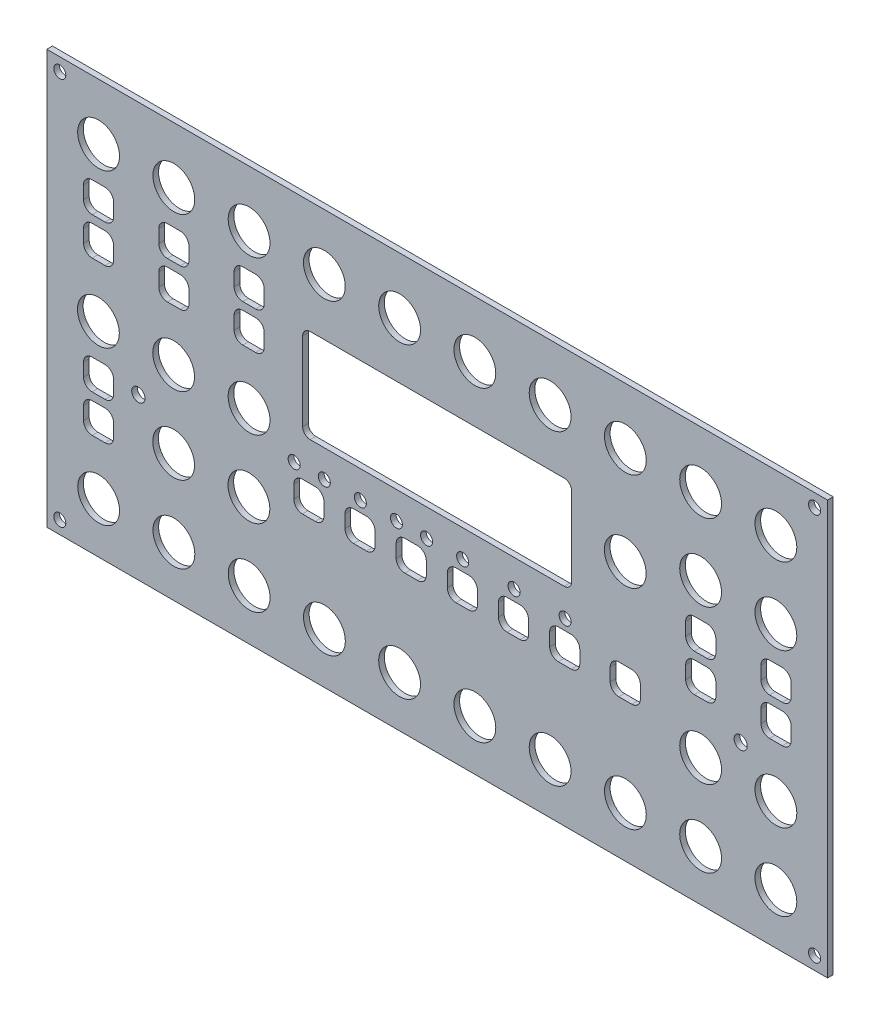
SolidWorks part; units mm, degrees
ref_plane "Спереди" through (0, 0, 0) normal (0, 0, 1) x (1, 0, 0)
ref_plane "Сверху" through (0, 0, 0) normal (0, 1, 0) x (1, 0, 0)
ref_plane "Справа" through (0, 0, 0) normal (1, 0, 0) x (0, 0, -1)
sketch "Model" plane through (0, 0, 0) normal (0, 0, 1) x (1, 0, 0)
  line L0 (-40.1364, 28.1427) -> (27.3636, 28.1427)
  line L1 (29.3636, 26.1427) -> (29.3636, 5.2508)
  line L2 (27.3636, 3.2508) -> (-40.1364, 3.2508)
  line L3 (-42.1364, 5.2508) -> (-42.1364, 26.1427)
  line L4 (-94.6584, 34.0806) -> (-98.087, 34.0806)
  line L5 (-100.3727, 31.7949) -> (-100.3727, 28.3663)
  line L6 (-98.087, 26.0806) -> (-94.6584, 26.0806)
  line L7 (-92.3727, 28.3663) -> (-92.3727, 31.7949)
  line L8 (-94.6584, 24.0706) -> (-98.087, 24.0706)
  line L9 (-100.3727, 21.7849) -> (-100.3727, 18.3563)
  line L10 (-98.087, 16.0706) -> (-94.6584, 16.0706)
  line L11 (-92.3727, 18.3563) -> (-92.3727, 21.7849)
  line L12 (-74.6595, 33.9889) -> (-78.0881, 33.9889)
  line L13 (-80.3738, 31.7032) -> (-80.3738, 28.2746)
  line L14 (-78.0881, 25.9889) -> (-74.6595, 25.9889)
  line L15 (-72.3738, 28.2746) -> (-72.3738, 31.7032)
  line L16 (-74.6595, 23.9789) -> (-78.0881, 23.9789)
  line L17 (-80.3738, 21.6932) -> (-80.3738, 18.2646)
  line L18 (-78.0881, 15.9789) -> (-74.6595, 15.9789)
  line L19 (-72.3738, 18.2646) -> (-72.3738, 21.6932)
  line L20 (-54.6394, 34.0718) -> (-58.068, 34.0718)
  line L21 (-60.3537, 31.7861) -> (-60.3537, 28.3575)
  line L22 (-58.068, 26.0718) -> (-54.6394, 26.0718)
  line L23 (-52.3537, 28.3575) -> (-52.3537, 31.7861)
  line L24 (-54.6394, 24.0618) -> (-58.068, 24.0618)
  line L25 (-60.3537, 21.7761) -> (-60.3537, 18.3475)
  line L26 (-58.068, 16.0618) -> (-54.6394, 16.0618)
  line L27 (-52.3537, 18.3475) -> (-52.3537, 21.7761)
  line L28 (-94.6584, -6.7301) -> (-98.087, -6.7301)
  line L29 (-100.3727, -9.0158) -> (-100.3727, -12.4444)
  line L30 (-98.087, -14.7301) -> (-94.6584, -14.7301)
  line L31 (-92.3727, -12.4444) -> (-92.3727, -9.0158)
  line L32 (-94.6584, -16.7401) -> (-98.087, -16.7401)
  line L33 (-100.3727, -19.0258) -> (-100.3727, -22.4544)
  line L34 (-98.087, -24.7401) -> (-94.6584, -24.7401)
  line L35 (-92.3727, -22.4544) -> (-92.3727, -19.0258)
  line L36 (65.3718, 13.632) -> (61.9432, 13.632)
  line L37 (59.6575, 11.3463) -> (59.6575, 7.9177)
  line L38 (61.9432, 5.632) -> (65.3718, 5.632)
  line L39 (67.6575, 7.9177) -> (67.6575, 11.3463)
  line L40 (65.3718, 3.622) -> (61.9432, 3.622)
  line L41 (59.6575, 1.3363) -> (59.6575, -2.0923)
  line L42 (61.9432, -4.378) -> (65.3718, -4.378)
  line L43 (67.6575, -2.0923) -> (67.6575, 1.3363)
  line L44 (85.3707, 13.5403) -> (81.9421, 13.5403)
  line L45 (79.6564, 11.2546) -> (79.6564, 7.826)
  line L46 (81.9421, 5.5403) -> (85.3707, 5.5403)
  line L47 (87.6564, 7.826) -> (87.6564, 11.2546)
  line L48 (85.3707, 3.5303) -> (81.9421, 3.5303)
  line L49 (79.6564, 1.2446) -> (79.6564, -2.184)
  line L50 (81.9421, -4.4697) -> (85.3707, -4.4697)
  line L51 (87.6564, -2.184) -> (87.6564, 1.2446)
  line L52 (-38.7751, -6.8889) -> (-42.2037, -6.8889)
  line L53 (-44.4894, -9.1746) -> (-44.4894, -12.6032)
  line L54 (-42.2037, -14.8889) -> (-38.7751, -14.8889)
  line L55 (-36.4894, -12.6032) -> (-36.4894, -9.1746)
  line L56 (-25.179, -6.8889) -> (-28.6076, -6.8889)
  line L57 (-30.8933, -9.1746) -> (-30.8933, -12.6032)
  line L58 (-28.6076, -14.8889) -> (-25.179, -14.8889)
  line L59 (-22.8933, -12.6032) -> (-22.8933, -9.1746)
  line L60 (-11.5688, -6.8889) -> (-14.9974, -6.8889)
  line L61 (-17.2831, -9.1746) -> (-17.2831, -12.6032)
  line L62 (-14.9974, -14.8889) -> (-11.5688, -14.8889)
  line L63 (-9.2831, -12.6032) -> (-9.2831, -9.1746)
  line L64 (2.0273, -6.8889) -> (-1.4013, -6.8889)
  line L65 (-3.687, -9.1746) -> (-3.687, -12.6032)
  line L66 (-1.4013, -14.8889) -> (2.0273, -14.8889)
  line L67 (4.313, -12.6032) -> (4.313, -9.1746)
  line L68 (15.6214, -6.8889) -> (12.1928, -6.8889)
  line L69 (9.9071, -9.1746) -> (9.9071, -12.6032)
  line L70 (12.1928, -14.8889) -> (15.6214, -14.8889)
  line L71 (17.9071, -12.6032) -> (17.9071, -9.1746)
  line L72 (29.2175, -6.8889) -> (25.7889, -6.8889)
  line L73 (23.5032, -9.1746) -> (23.5032, -12.6032)
  line L74 (25.7889, -14.8889) -> (29.2175, -14.8889)
  line L75 (31.5032, -12.6032) -> (31.5032, -9.1746)
  line L76 (45.311, -6.9101) -> (41.8824, -6.9101)
  line L77 (39.5967, -9.1958) -> (39.5967, -12.6244)
  line L78 (41.8824, -14.9101) -> (45.311, -14.9101)
  line L79 (47.5967, -12.6244) -> (47.5967, -9.1958)
  line L80 (-110.1377, -51.9034) -> (97.3623, -51.9034)
  line L81 (97.3623, -51.9034) -> (97.3623, 58.0966)
  line L82 (97.3623, 58.0966) -> (-110.1377, 58.0966)
  line L83 (-110.1377, 58.0966) -> (-110.1377, -51.9034)
  ellipse E0 centre (-96.3727, 43.142) end of major axis (-96.3727, 48.6983) minor radius 5.5563
  ellipse E1 centre (-76.3738, 43.142) end of major axis (-76.3738, 48.6983) minor radius 5.5563
  ellipse E2 centre (-96.4221, 2.3418) end of major axis (-96.4221, 7.8981) minor radius 5.5563
  ellipse E3 centre (-76.4232, 2.3418) end of major axis (-76.4232, 7.8981) minor radius 5.5563
  ellipse E4 centre (-96.3568, -38.4583) end of major axis (-96.3568, -32.902) minor radius 5.5563
  ellipse E5 centre (-76.3579, -38.4583) end of major axis (-76.3579, -32.902) minor radius 5.5563
  ellipse E6 centre (-56.3572, -38.4583) end of major axis (-56.3572, -32.902) minor radius 5.5563
  ellipse E7 centre (-36.3583, -38.4583) end of major axis (-36.3583, -32.902) minor radius 5.5563
  ellipse E8 centre (-16.3735, -38.4583) end of major axis (-16.3735, -32.902) minor radius 5.5563
  ellipse E9 centre (3.6254, -38.4583) end of major axis (9.1817, -38.4583) minor radius 5.5563
  ellipse E10 centre (23.6261, -38.4583) end of major axis (23.6261, -32.902) minor radius 5.5563
  ellipse E11 centre (43.625, -38.4583) end of major axis (43.625, -32.902) minor radius 5.5563
  ellipse E12 centre (63.6257, -38.4583) end of major axis (63.6257, -32.902) minor radius 5.5563
  ellipse E13 centre (63.6257, -18.0591) end of major axis (63.6257, -12.5028) minor radius 5.5563
  ellipse E14 centre (83.6246, -18.0591) end of major axis (83.6246, -12.5028) minor radius 5.5563
  ellipse E15 centre (63.6257, 22.7411) end of major axis (63.6257, 28.2974) minor radius 5.5563
  ellipse E16 centre (83.6246, 22.7411) end of major axis (83.6246, 28.2974) minor radius 5.5563
  ellipse E17 centre (63.6257, 43.142) end of major axis (63.6257, 48.6983) minor radius 5.5563
  ellipse E18 centre (83.6246, 43.142) end of major axis (83.6246, 48.6983) minor radius 5.5563
  ellipse E19 centre (23.6261, 43.142) end of major axis (23.6261, 48.6983) minor radius 5.5563
  ellipse E20 centre (43.625, 43.142) end of major axis (43.625, 48.6983) minor radius 5.5563
  ellipse E21 centre (-16.3735, 43.142) end of major axis (-16.3735, 48.6983) minor radius 5.5563
  ellipse E22 centre (3.6254, 43.142) end of major axis (9.1817, 43.142) minor radius 5.5563
  ellipse E23 centre (-76.4215, -18.0591) end of major axis (-76.4215, -12.5028) minor radius 5.5563
  ellipse E24 centre (-56.4226, -18.0591) end of major axis (-56.4226, -12.5028) minor radius 5.5563
  ellipse E25 centre (-56.3731, 43.142) end of major axis (-56.3731, 48.6983) minor radius 5.5563
  ellipse E26 centre (-36.3742, 43.142) end of major axis (-36.3742, 48.6983) minor radius 5.5563
  ellipse E27 centre (-56.3749, 2.3418) end of major axis (-56.3749, 7.8981) minor radius 5.5563
  ellipse E28 centre (43.5968, 17.0508) end of major axis (43.5968, 22.6071) minor radius 5.5563
  ellipse E29 centre (-85.8018, -9.238) end of major axis (-87.5674, -9.238) minor radius 1.7656
  ellipse E30 centre (-106.6826, 54.6408) end of major axis (-108.2826, 54.6408) minor radius 1.6
  ellipse E31 centre (-106.6826, -48.4638) end of major axis (-108.2826, -48.4638) minor radius 1.6
  ellipse E32 centre (93.8945, 54.6408) end of major axis (92.2945, 54.6408) minor radius 1.6
  ellipse E33 centre (74.262, -9.238) end of major axis (72.512, -9.238) minor radius 1.75
  ellipse E34 centre (-44.3965, -4.0453) end of major axis (-44.3965, -2.4453) minor radius 1.6
  ellipse E35 centre (-36.3796, -4.0453) end of major axis (-36.3796, -2.4453) minor radius 1.6
  ellipse E36 centre (-26.8017, -4.0453) end of major axis (-28.4017, -4.0453) minor radius 1.6
  ellipse E37 centre (-17.2236, -4.0453) end of major axis (-18.8236, -4.0453) minor radius 1.6
  ellipse E38 centre (-9.2066, -4.0453) end of major axis (-10.8066, -4.0453) minor radius 1.6
  ellipse E39 centre (0.3845, -4.0453) end of major axis (-1.2155, -4.0453) minor radius 1.6
  ellipse E40 centre (14.037, -4.0453) end of major axis (12.437, -4.0453) minor radius 1.6
  ellipse E41 centre (27.6102, -4.0453) end of major axis (26.0102, -4.0453) minor radius 1.6
  ellipse E42 centre (83.6246, -38.4583) end of major axis (83.6246, -32.902) minor radius 5.5563
  ellipse E43 centre (93.8945, -48.4638) end of major axis (92.2945, -48.4638) minor radius 1.6
  spline S0 degree 3 poles (27.3636, 28.1427) (28.4636, 28.1427) (29.3636, 27.2427) (29.3636, 26.1427) knots 0.111111 0.111111 0.111111 0.111111 0.222222 0.222222 0.222222 0.222222
  spline S1 degree 3 poles (29.3636, 5.2508) (29.3636, 4.1508) (28.4636, 3.2508) (27.3636, 3.2508) knots 0.333333 0.333333 0.333333 0.333333 0.444444 0.444444 0.444444 0.444444
  spline S2 degree 3 poles (-40.1364, 3.2508) (-41.2364, 3.2508) (-42.1364, 4.1508) (-42.1364, 5.2508) knots 0.555556 0.555556 0.555556 0.555556 0.666667 0.666667 0.666667 0.666667
  spline S3 degree 3 poles (-42.1364, 26.1427) (-42.1364, 27.2427) (-41.2364, 28.1427) (-40.1364, 28.1427) knots 0.777778 0.777778 0.777778 0.777778 1 1 1 1
  spline S4 degree 3 poles (-98.087, 34.0806) (-99.3442, 34.0806) (-100.3727, 33.0521) (-100.3727, 31.7949) knots 0.111111 0.111111 0.111111 0.111111 0.222222 0.222222 0.222222 0.222222
  spline S5 degree 3 poles (-100.3727, 28.3663) (-100.3727, 27.1091) (-99.3442, 26.0806) (-98.087, 26.0806) knots 0.333333 0.333333 0.333333 0.333333 0.444444 0.444444 0.444444 0.444444
  spline S6 degree 3 poles (-94.6584, 26.0806) (-93.4012, 26.0806) (-92.3727, 27.1091) (-92.3727, 28.3663) knots 0.555556 0.555556 0.555556 0.555556 0.666667 0.666667 0.666667 0.666667
  spline S7 degree 3 poles (-92.3727, 31.7949) (-92.3727, 33.0521) (-93.4012, 34.0806) (-94.6584, 34.0806) knots 0.777778 0.777778 0.777778 0.777778 1 1 1 1
  spline S8 degree 3 poles (-98.087, 24.0706) (-99.3442, 24.0706) (-100.3727, 23.0421) (-100.3727, 21.7849) knots 0.111111 0.111111 0.111111 0.111111 0.222222 0.222222 0.222222 0.222222
  spline S9 degree 3 poles (-100.3727, 18.3563) (-100.3727, 17.0991) (-99.3442, 16.0706) (-98.087, 16.0706) knots 0.333333 0.333333 0.333333 0.333333 0.444444 0.444444 0.444444 0.444444
  spline S10 degree 3 poles (-94.6584, 16.0706) (-93.4012, 16.0706) (-92.3727, 17.0991) (-92.3727, 18.3563) knots 0.555556 0.555556 0.555556 0.555556 0.666667 0.666667 0.666667 0.666667
  spline S11 degree 3 poles (-92.3727, 21.7849) (-92.3727, 23.0421) (-93.4012, 24.0706) (-94.6584, 24.0706) knots 0.777778 0.777778 0.777778 0.777778 1 1 1 1
  spline S12 degree 3 poles (-78.0881, 33.9889) (-79.3453, 33.9889) (-80.3738, 32.9604) (-80.3738, 31.7032) knots 0.111111 0.111111 0.111111 0.111111 0.222222 0.222222 0.222222 0.222222
  spline S13 degree 3 poles (-80.3738, 28.2746) (-80.3738, 27.0174) (-79.3453, 25.9889) (-78.0881, 25.9889) knots 0.333333 0.333333 0.333333 0.333333 0.444444 0.444444 0.444444 0.444444
  spline S14 degree 3 poles (-74.6595, 25.9889) (-73.4023, 25.9889) (-72.3738, 27.0174) (-72.3738, 28.2746) knots 0.555556 0.555556 0.555556 0.555556 0.666667 0.666667 0.666667 0.666667
  spline S15 degree 3 poles (-72.3738, 31.7032) (-72.3738, 32.9604) (-73.4023, 33.9889) (-74.6595, 33.9889) knots 0.777778 0.777778 0.777778 0.777778 1 1 1 1
  spline S16 degree 3 poles (-78.0881, 23.9789) (-79.3453, 23.9789) (-80.3738, 22.9504) (-80.3738, 21.6932) knots 0.111111 0.111111 0.111111 0.111111 0.222222 0.222222 0.222222 0.222222
  spline S17 degree 3 poles (-80.3738, 18.2646) (-80.3738, 17.0074) (-79.3453, 15.9789) (-78.0881, 15.9789) knots 0.333333 0.333333 0.333333 0.333333 0.444444 0.444444 0.444444 0.444444
  spline S18 degree 3 poles (-74.6595, 15.9789) (-73.4023, 15.9789) (-72.3738, 17.0074) (-72.3738, 18.2646) knots 0.555556 0.555556 0.555556 0.555556 0.666667 0.666667 0.666667 0.666667
  spline S19 degree 3 poles (-72.3738, 21.6932) (-72.3738, 22.9504) (-73.4023, 23.9789) (-74.6595, 23.9789) knots 0.777778 0.777778 0.777778 0.777778 1 1 1 1
  spline S20 degree 3 poles (-58.068, 34.0718) (-59.3252, 34.0718) (-60.3537, 33.0433) (-60.3537, 31.7861) knots 0.111111 0.111111 0.111111 0.111111 0.222222 0.222222 0.222222 0.222222
  spline S21 degree 3 poles (-60.3537, 28.3575) (-60.3537, 27.1003) (-59.3252, 26.0718) (-58.068, 26.0718) knots 0.333333 0.333333 0.333333 0.333333 0.444444 0.444444 0.444444 0.444444
  spline S22 degree 3 poles (-54.6394, 26.0718) (-53.3822, 26.0718) (-52.3537, 27.1003) (-52.3537, 28.3575) knots 0.555556 0.555556 0.555556 0.555556 0.666667 0.666667 0.666667 0.666667
  spline S23 degree 3 poles (-52.3537, 31.7861) (-52.3537, 33.0433) (-53.3822, 34.0718) (-54.6394, 34.0718) knots 0.777778 0.777778 0.777778 0.777778 1 1 1 1
  spline S24 degree 3 poles (-58.068, 24.0618) (-59.3252, 24.0618) (-60.3537, 23.0333) (-60.3537, 21.7761) knots 0.111111 0.111111 0.111111 0.111111 0.222222 0.222222 0.222222 0.222222
  spline S25 degree 3 poles (-60.3537, 18.3475) (-60.3537, 17.0903) (-59.3252, 16.0618) (-58.068, 16.0618) knots 0.333333 0.333333 0.333333 0.333333 0.444444 0.444444 0.444444 0.444444
  spline S26 degree 3 poles (-54.6394, 16.0618) (-53.3822, 16.0618) (-52.3537, 17.0903) (-52.3537, 18.3475) knots 0.555556 0.555556 0.555556 0.555556 0.666667 0.666667 0.666667 0.666667
  spline S27 degree 3 poles (-52.3537, 21.7761) (-52.3537, 23.0333) (-53.3822, 24.0618) (-54.6394, 24.0618) knots 0.777778 0.777778 0.777778 0.777778 1 1 1 1
  spline S28 degree 3 poles (-98.087, -6.7301) (-99.3442, -6.7301) (-100.3727, -7.7586) (-100.3727, -9.0158) knots 0.111111 0.111111 0.111111 0.111111 0.222222 0.222222 0.222222 0.222222
  spline S29 degree 3 poles (-100.3727, -12.4444) (-100.3727, -13.7016) (-99.3442, -14.7301) (-98.087, -14.7301) knots 0.333333 0.333333 0.333333 0.333333 0.444444 0.444444 0.444444 0.444444
  spline S30 degree 3 poles (-94.6584, -14.7301) (-93.4012, -14.7301) (-92.3727, -13.7016) (-92.3727, -12.4444) knots 0.555556 0.555556 0.555556 0.555556 0.666667 0.666667 0.666667 0.666667
  spline S31 degree 3 poles (-92.3727, -9.0158) (-92.3727, -7.7586) (-93.4012, -6.7301) (-94.6584, -6.7301) knots 0.777778 0.777778 0.777778 0.777778 1 1 1 1
  spline S32 degree 3 poles (-98.087, -16.7401) (-99.3442, -16.7401) (-100.3727, -17.7686) (-100.3727, -19.0258) knots 0.111111 0.111111 0.111111 0.111111 0.222222 0.222222 0.222222 0.222222
  spline S33 degree 3 poles (-100.3727, -22.4544) (-100.3727, -23.7116) (-99.3442, -24.7401) (-98.087, -24.7401) knots 0.333333 0.333333 0.333333 0.333333 0.444444 0.444444 0.444444 0.444444
  spline S34 degree 3 poles (-94.6584, -24.7401) (-93.4012, -24.7401) (-92.3727, -23.7116) (-92.3727, -22.4544) knots 0.555556 0.555556 0.555556 0.555556 0.666667 0.666667 0.666667 0.666667
  spline S35 degree 3 poles (-92.3727, -19.0258) (-92.3727, -17.7686) (-93.4012, -16.7401) (-94.6584, -16.7401) knots 0.777778 0.777778 0.777778 0.777778 1 1 1 1
  spline S36 degree 3 poles (61.9432, 13.632) (60.686, 13.632) (59.6575, 12.6035) (59.6575, 11.3463) knots 0.111111 0.111111 0.111111 0.111111 0.222222 0.222222 0.222222 0.222222
  spline S37 degree 3 poles (59.6575, 7.9177) (59.6575, 6.6605) (60.686, 5.632) (61.9432, 5.632) knots 0.333333 0.333333 0.333333 0.333333 0.444444 0.444444 0.444444 0.444444
  spline S38 degree 3 poles (65.3718, 5.632) (66.629, 5.632) (67.6575, 6.6605) (67.6575, 7.9177) knots 0.555556 0.555556 0.555556 0.555556 0.666667 0.666667 0.666667 0.666667
  spline S39 degree 3 poles (67.6575, 11.3463) (67.6575, 12.6035) (66.629, 13.632) (65.3718, 13.632) knots 0.777778 0.777778 0.777778 0.777778 1 1 1 1
  spline S40 degree 3 poles (61.9432, 3.622) (60.686, 3.622) (59.6575, 2.5935) (59.6575, 1.3363) knots 0.111111 0.111111 0.111111 0.111111 0.222222 0.222222 0.222222 0.222222
  spline S41 degree 3 poles (59.6575, -2.0923) (59.6575, -3.3495) (60.686, -4.378) (61.9432, -4.378) knots 0.333333 0.333333 0.333333 0.333333 0.444444 0.444444 0.444444 0.444444
  spline S42 degree 3 poles (65.3718, -4.378) (66.629, -4.378) (67.6575, -3.3495) (67.6575, -2.0923) knots 0.555556 0.555556 0.555556 0.555556 0.666667 0.666667 0.666667 0.666667
  spline S43 degree 3 poles (67.6575, 1.3363) (67.6575, 2.5935) (66.629, 3.622) (65.3718, 3.622) knots 0.777778 0.777778 0.777778 0.777778 1 1 1 1
  spline S44 degree 3 poles (81.9421, 13.5403) (80.6849, 13.5403) (79.6564, 12.5118) (79.6564, 11.2546) knots 0.111111 0.111111 0.111111 0.111111 0.222222 0.222222 0.222222 0.222222
  spline S45 degree 3 poles (79.6564, 7.826) (79.6564, 6.5688) (80.6849, 5.5403) (81.9421, 5.5403) knots 0.333333 0.333333 0.333333 0.333333 0.444444 0.444444 0.444444 0.444444
  spline S46 degree 3 poles (85.3707, 5.5403) (86.6279, 5.5403) (87.6564, 6.5688) (87.6564, 7.826) knots 0.555556 0.555556 0.555556 0.555556 0.666667 0.666667 0.666667 0.666667
  spline S47 degree 3 poles (87.6564, 11.2546) (87.6564, 12.5118) (86.6279, 13.5403) (85.3707, 13.5403) knots 0.777778 0.777778 0.777778 0.777778 1 1 1 1
  spline S48 degree 3 poles (81.9421, 3.5303) (80.6849, 3.5303) (79.6564, 2.5018) (79.6564, 1.2446) knots 0.111111 0.111111 0.111111 0.111111 0.222222 0.222222 0.222222 0.222222
  spline S49 degree 3 poles (79.6564, -2.184) (79.6564, -3.4412) (80.6849, -4.4697) (81.9421, -4.4697) knots 0.333333 0.333333 0.333333 0.333333 0.444444 0.444444 0.444444 0.444444
  spline S50 degree 3 poles (85.3707, -4.4697) (86.6279, -4.4697) (87.6564, -3.4412) (87.6564, -2.184) knots 0.555556 0.555556 0.555556 0.555556 0.666667 0.666667 0.666667 0.666667
  spline S51 degree 3 poles (87.6564, 1.2446) (87.6564, 2.5018) (86.6279, 3.5303) (85.3707, 3.5303) knots 0.777778 0.777778 0.777778 0.777778 1 1 1 1
  spline S52 degree 3 poles (-42.2037, -6.8889) (-43.4609, -6.8889) (-44.4894, -7.9174) (-44.4894, -9.1746) knots 0.111111 0.111111 0.111111 0.111111 0.222222 0.222222 0.222222 0.222222
  spline S53 degree 3 poles (-44.4894, -12.6032) (-44.4894, -13.8604) (-43.4609, -14.8889) (-42.2037, -14.8889) knots 0.333333 0.333333 0.333333 0.333333 0.444444 0.444444 0.444444 0.444444
  spline S54 degree 3 poles (-38.7751, -14.8889) (-37.5179, -14.8889) (-36.4894, -13.8604) (-36.4894, -12.6032) knots 0.555556 0.555556 0.555556 0.555556 0.666667 0.666667 0.666667 0.666667
  spline S55 degree 3 poles (-36.4894, -9.1746) (-36.4894, -7.9174) (-37.5179, -6.8889) (-38.7751, -6.8889) knots 0.777778 0.777778 0.777778 0.777778 1 1 1 1
  spline S56 degree 3 poles (-28.6076, -6.8889) (-29.8648, -6.8889) (-30.8933, -7.9174) (-30.8933, -9.1746) knots 0.111111 0.111111 0.111111 0.111111 0.222222 0.222222 0.222222 0.222222
  spline S57 degree 3 poles (-30.8933, -12.6032) (-30.8933, -13.8604) (-29.8648, -14.8889) (-28.6076, -14.8889) knots 0.333333 0.333333 0.333333 0.333333 0.444444 0.444444 0.444444 0.444444
  spline S58 degree 3 poles (-25.179, -14.8889) (-23.9218, -14.8889) (-22.8933, -13.8604) (-22.8933, -12.6032) knots 0.555556 0.555556 0.555556 0.555556 0.666667 0.666667 0.666667 0.666667
  spline S59 degree 3 poles (-22.8933, -9.1746) (-22.8933, -7.9174) (-23.9218, -6.8889) (-25.179, -6.8889) knots 0.777778 0.777778 0.777778 0.777778 1 1 1 1
  spline S60 degree 3 poles (-14.9974, -6.8889) (-16.2546, -6.8889) (-17.2831, -7.9174) (-17.2831, -9.1746) knots 0.111111 0.111111 0.111111 0.111111 0.222222 0.222222 0.222222 0.222222
  spline S61 degree 3 poles (-17.2831, -12.6032) (-17.2831, -13.8604) (-16.2546, -14.8889) (-14.9974, -14.8889) knots 0.333333 0.333333 0.333333 0.333333 0.444444 0.444444 0.444444 0.444444
  spline S62 degree 3 poles (-11.5688, -14.8889) (-10.3116, -14.8889) (-9.2831, -13.8604) (-9.2831, -12.6032) knots 0.555556 0.555556 0.555556 0.555556 0.666667 0.666667 0.666667 0.666667
  spline S63 degree 3 poles (-9.2831, -9.1746) (-9.2831, -7.9174) (-10.3116, -6.8889) (-11.5688, -6.8889) knots 0.777778 0.777778 0.777778 0.777778 1 1 1 1
  spline S64 degree 3 poles (-1.4013, -6.8889) (-2.6585, -6.8889) (-3.687, -7.9174) (-3.687, -9.1746) knots 0.111111 0.111111 0.111111 0.111111 0.222222 0.222222 0.222222 0.222222
  spline S65 degree 3 poles (-3.687, -12.6032) (-3.687, -13.8604) (-2.6585, -14.8889) (-1.4013, -14.8889) knots 0.333333 0.333333 0.333333 0.333333 0.444444 0.444444 0.444444 0.444444
  spline S66 degree 3 poles (2.0273, -14.8889) (3.2845, -14.8889) (4.313, -13.8604) (4.313, -12.6032) knots 0.555556 0.555556 0.555556 0.555556 0.666667 0.666667 0.666667 0.666667
  spline S67 degree 3 poles (4.313, -9.1746) (4.313, -7.9174) (3.2845, -6.8889) (2.0273, -6.8889) knots 0.777778 0.777778 0.777778 0.777778 1 1 1 1
  spline S68 degree 3 poles (12.1928, -6.8889) (10.9356, -6.8889) (9.9071, -7.9174) (9.9071, -9.1746) knots 0.111111 0.111111 0.111111 0.111111 0.222222 0.222222 0.222222 0.222222
  spline S69 degree 3 poles (9.9071, -12.6032) (9.9071, -13.8604) (10.9356, -14.8889) (12.1928, -14.8889) knots 0.333333 0.333333 0.333333 0.333333 0.444444 0.444444 0.444444 0.444444
  spline S70 degree 3 poles (15.6214, -14.8889) (16.8786, -14.8889) (17.9071, -13.8604) (17.9071, -12.6032) knots 0.555556 0.555556 0.555556 0.555556 0.666667 0.666667 0.666667 0.666667
  spline S71 degree 3 poles (17.9071, -9.1746) (17.9071, -7.9174) (16.8786, -6.8889) (15.6214, -6.8889) knots 0.777778 0.777778 0.777778 0.777778 1 1 1 1
  spline S72 degree 3 poles (25.7889, -6.8889) (24.5317, -6.8889) (23.5032, -7.9174) (23.5032, -9.1746) knots 0.111111 0.111111 0.111111 0.111111 0.222222 0.222222 0.222222 0.222222
  spline S73 degree 3 poles (23.5032, -12.6032) (23.5032, -13.8604) (24.5317, -14.8889) (25.7889, -14.8889) knots 0.333333 0.333333 0.333333 0.333333 0.444444 0.444444 0.444444 0.444444
  spline S74 degree 3 poles (29.2175, -14.8889) (30.4747, -14.8889) (31.5032, -13.8604) (31.5032, -12.6032) knots 0.555556 0.555556 0.555556 0.555556 0.666667 0.666667 0.666667 0.666667
  spline S75 degree 3 poles (31.5032, -9.1746) (31.5032, -7.9174) (30.4747, -6.8889) (29.2175, -6.8889) knots 0.777778 0.777778 0.777778 0.777778 1 1 1 1
  spline S76 degree 3 poles (41.8824, -6.9101) (40.6252, -6.9101) (39.5967, -7.9386) (39.5967, -9.1958) knots 0.111111 0.111111 0.111111 0.111111 0.222222 0.222222 0.222222 0.222222
  spline S77 degree 3 poles (39.5967, -12.6244) (39.5967, -13.8816) (40.6252, -14.9101) (41.8824, -14.9101) knots 0.333333 0.333333 0.333333 0.333333 0.444444 0.444444 0.444444 0.444444
  spline S78 degree 3 poles (45.311, -14.9101) (46.5682, -14.9101) (47.5967, -13.8816) (47.5967, -12.6244) knots 0.555556 0.555556 0.555556 0.555556 0.666667 0.666667 0.666667 0.666667
  spline S79 degree 3 poles (47.5967, -9.1958) (47.5967, -7.9386) (46.5682, -6.9101) (45.311, -6.9101) knots 0.777778 0.777778 0.777778 0.777778 1 1 1 1
extrude "Бобышка-Вытянуть1" add sketch "Model" along normal blind 1.5
